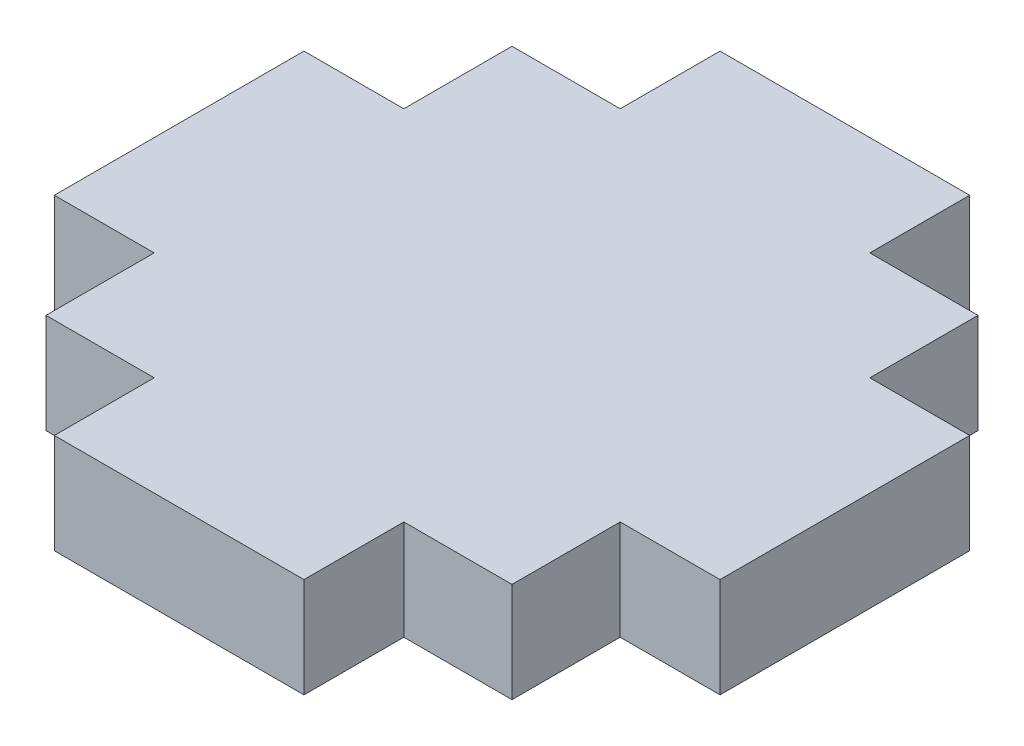
SolidWorks part; units mm, degrees
ref_plane "Alzado" through (0, 0, 0) normal (0, 0, 1) x (1, 0, 0)
ref_plane "Planta" through (0, 0, 0) normal (0, 1, 0) x (1, 0, 0)
ref_plane "Vista lateral" through (0, 0, 0) normal (1, 0, 0) x (0, 0, -1)
sketch "Croquis1" plane through (0, 0, 0) normal (0, 1, 0) x (1, 0, 0)
  line L0 (12.5, 40) -> (12.5, 34)
  line L1 (0, 0) -> (40, 0)
  line L2 (0, 0) -> (0, 40)
  line L3 (0, 40) -> (40, 40)
  line L4 (40, 0) -> (40, 40)
  line L5 (12.5, 34) -> (6, 34)
  line L6 (6, 34) -> (6, 27.5)
  line L7 (6, 27.5) -> (0, 27.5)
  line L8 (20, 40) -> (20, 0) construction
  line L9 (0, 20) -> (40, 20) construction
  line L10 (6, 12.5) -> (0, 12.5)
  line L11 (6, 6) -> (6, 12.5)
  line L12 (12.5, 6) -> (6, 6)
  line L13 (12.5, 0) -> (12.5, 6)
  line L14 (27.5, 40) -> (27.5, 34)
  line L15 (27.5, 34) -> (34, 34)
  line L16 (34, 34) -> (34, 27.5)
  line L17 (34, 27.5) -> (40, 27.5)
  line L18 (34, 12.5) -> (40, 12.5)
  line L19 (34, 6) -> (34, 12.5)
  line L20 (27.5, 0) -> (27.5, 6)
  line L21 (27.5, 6) -> (34, 6)
  dimension "D1" = 40
  dimension "D2" = 40
  dimension "D3" = 6
  dimension "D4" = 12.5
extrude "Saliente-Extruir1" add sketch "Croquis1" along normal blind 6
